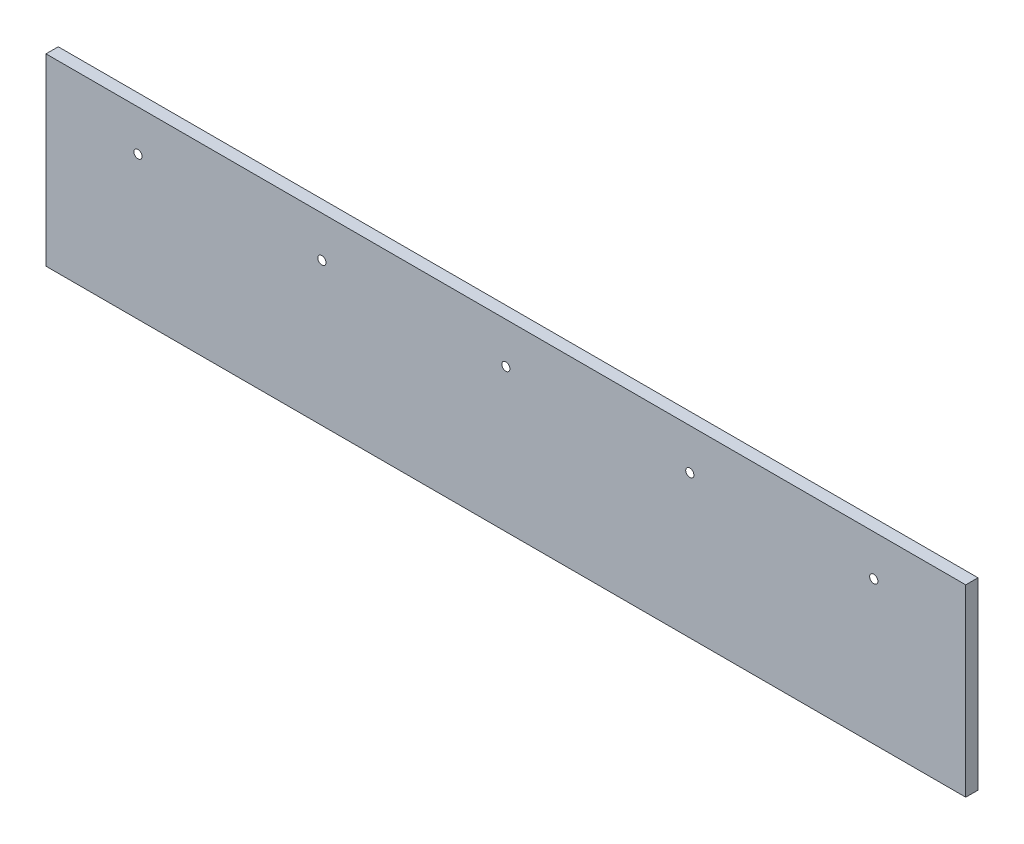
SolidWorks part; units mm, degrees
ref_plane "Front Plane" through (0, 0, 0) normal (0, 0, 1) x (1, 0, 0)
ref_plane "Top Plane" through (0, 0, 0) normal (0, 1, 0) x (1, 0, 0)
ref_plane "Right Plane" through (0, 0, 0) normal (1, 0, 0) x (0, 0, -1)
sketch "Sketch1" plane through (0, 0, 0) normal (0, 0, 1) x (1, 0, 0)
  line L0 (-112.5, 12.5) -> (112.5, 12.5) construction
  line L1 (-112.5, -22.5) -> (112.5, -22.5)
  line L2 (-112.5, -22.5) -> (-112.5, 22.5)
  line L3 (-112.5, 22.5) -> (112.5, 22.5)
  line L4 (112.5, -22.5) -> (112.5, 22.5)
  line L5 (-112.5, -22.5) -> (112.5, 22.5) construction
  line L6 (-112.5, 22.5) -> (112.5, -22.5) construction
  line L7 (-112.5, -22.5) -> (112.5, -22.5)
  line L8 (-112.5, -22.5) -> (-112.5, 7.5)
  line L9 (-112.5, 7.5) -> (112.5, 7.5) construction
  line L10 (112.5, -22.5) -> (112.5, 7.5)
  circle A0 centre (0, 12.5) radius 1
  circle A1 centre (45, 12.5) radius 1
  circle A2 centre (90, 12.5) radius 1
  circle A3 centre (-45, 12.5) radius 1
  circle A4 centre (-90, 12.5) radius 1
  point P0 (0, 0)
  dimension "D9" = 2
  dimension "D1" = 225
  dimension "D2" = 5
  dimension "D3" = 30
  dimension "D4" = 10
  dimension "D5" = 45
  dimension "D6" = 45
  dimension "D7" = 45
  dimension "D8" = 45
extrude "Boss-Extrude1" add sketch "Sketch1" along normal blind 3 contours L1 L4 L3 L2
draft "Draft3" type of draft neutral plane draft angle 60 faces to draft 5 face at (91, 12.5, 3) face at (46, 12.5, 3) face at (1, 12.5, 3) face at (-44, 12.5, 3) face at (-89, 12.5, 3) neutral plane through (0, 0, 3) neutral plane normal (0, 0, 1) reverse direction yes parameters "D1"=60
equation "\"Scaled Distance\"= 1.5m"
equation "\"Normal Distance\"= 25m"
equation "\"Scale Factor\"= \"Normal Distance\" / \"Scaled Distance\""
equation "\"Scaled Target\"= 500 / \"Scale Factor\""
